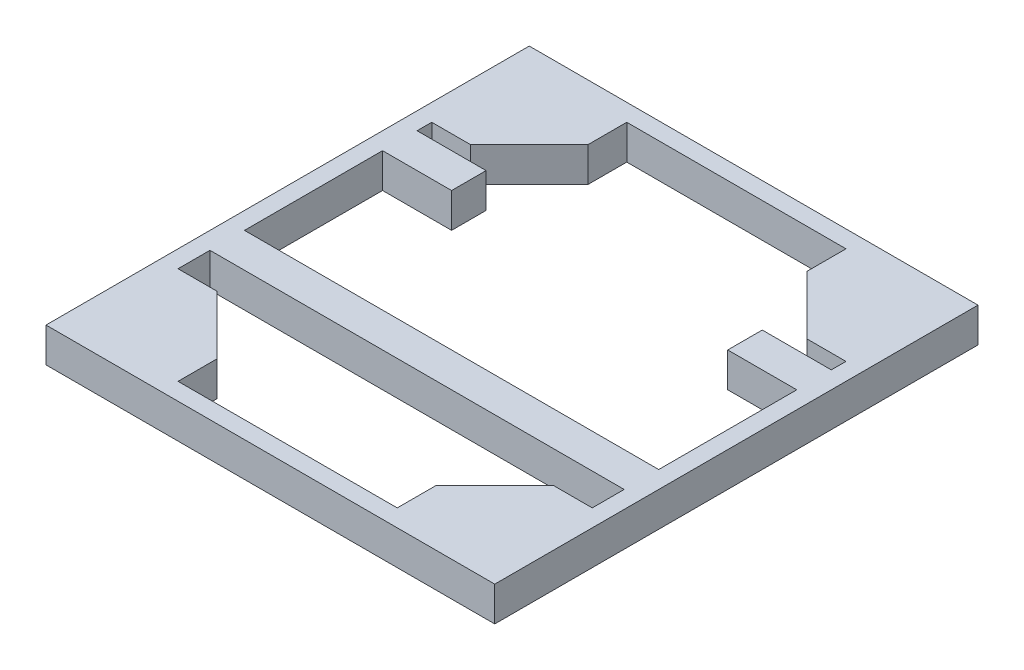
SolidWorks part; units mm, degrees
ref_plane "Front Plane" through (0, 0, 0) normal (0, 0, 1) x (1, 0, 0)
ref_plane "Top Plane" through (0, 0, 0) normal (0, 1, 0) x (1, 0, 0)
ref_plane "Right Plane" through (0, 0, 0) normal (1, 0, 0) x (0, 0, -1)
sketch "Sketch1" plane through (0, 0, 0) normal (0, 1, 0) x (1, 0, 0)
  line L0 (82.55, 542.3028) -> (168.8972, 628.65)
  line L1 (0, 0) -> (660.4, 0)
  line L2 (0, 0) -> (0, 711.2)
  line L3 (0, 711.2) -> (660.4, 711.2)
  line L4 (660.4, 0) -> (660.4, 711.2)
  line L5 (25.4, 685.8) -> (635, 685.8)
  line L6 (25.4, 685.8) -> (25.4, 25.4)
  line L7 (25.4, 25.4) -> (635, 25.4)
  line L8 (635, 685.8) -> (635, 25.4)
  line L9 (82.55, 542.3028) -> (25.4, 542.3028)
  line L10 (168.8972, 628.65) -> (168.8972, 685.8)
  line L11 (330.2, 711.2) -> (330.2, 0) construction
  line L12 (0, 355.6) -> (660.4, 355.6) construction
  line L13 (82.55, 168.8972) -> (168.8972, 82.55)
  line L14 (168.8972, 82.55) -> (168.8972, 25.4)
  line L15 (82.55, 168.8972) -> (25.4, 168.8972)
  line L16 (491.5028, 628.65) -> (491.5028, 685.8)
  line L17 (577.85, 542.3028) -> (491.5028, 628.65)
  line L18 (577.85, 542.3028) -> (635, 542.3028)
  line L19 (577.85, 168.8972) -> (635, 168.8972)
  line L20 (491.5028, 82.55) -> (491.5028, 25.4)
  line L21 (577.85, 168.8972) -> (491.5028, 82.55)
  point P9 (330.2, 685.8)
  point P10 (330.2, 711.2)
  point P11 (635, 355.6)
  point P12 (660.4, 355.6)
  dimension "D1" = 660.4
  dimension "D2" = 711.2
  dimension "D3" = 25.4
  dimension "D4" = 25.4
  dimension "D5" = 177.8
  dimension "D6" = 57.15
  dimension "D7" = 57.15
  dimension "D8" = 45
extrude "Boss-Extrude1" add sketch "Sketch1" along normal blind 50.8 contours L0 L10 L5 L6 L9 | L17 L18 L8 L5 L16 | L19 L21 L20 L7 L8 | L13 L15 L6 L7 L14 | L1 L4 L3 L2 L5 L8 L7 L6
sketch "Sketch2" plane through (0, 50.8, 0) normal (0, 1, 0) x (1, 0, 0)
  line L1 (635, 215.9) -> (25.4, 215.9)
  line L2 (635, 215.9) -> (635, 266.7)
  line L3 (635, 266.7) -> (25.4, 266.7)
  line L4 (25.4, 215.9) -> (25.4, 266.7)
  line L5 (635, 469.9) -> (25.4, 469.9)
  line L6 (635, 469.9) -> (635, 520.7)
  line L7 (635, 520.7) -> (25.4, 520.7)
  line L8 (25.4, 469.9) -> (25.4, 520.7)
  line L16 (168.8972, 25.4) -> (491.5028, 25.4)
  line L17 (168.8972, 82.55) -> (168.8972, 25.4)
  line L18 (82.55, 168.8972) -> (168.8972, 82.55)
  line L19 (25.4, 168.8972) -> (82.55, 168.8972)
  line L20 (25.4, 542.3028) -> (25.4, 168.8972)
  line L21 (82.55, 542.3028) -> (25.4, 542.3028)
  line L22 (168.8972, 628.65) -> (82.55, 542.3028)
  line L23 (168.8972, 685.8) -> (168.8972, 628.65)
  line L24 (491.5028, 685.8) -> (168.8972, 685.8)
  line L25 (491.5028, 628.65) -> (491.5028, 685.8)
  line L26 (577.85, 542.3028) -> (491.5028, 628.65)
  line L27 (635, 542.3028) -> (577.85, 542.3028)
  line L28 (635, 168.8972) -> (635, 542.3028)
  line L29 (577.85, 168.8972) -> (635, 168.8972)
  line L30 (491.5028, 82.55) -> (577.85, 168.8972)
  line L31 (491.5028, 25.4) -> (491.5028, 82.55)
  line L32 (168.8972, 25.4) -> (491.5028, 25.4)
  line L33 (168.8972, 82.55) -> (168.8972, 25.4)
  line L34 (82.55, 168.8972) -> (168.8972, 82.55)
  line L35 (25.4, 168.8972) -> (82.55, 168.8972)
  line L36 (25.4, 542.3028) -> (25.4, 168.8972)
  line L37 (82.55, 542.3028) -> (25.4, 542.3028)
  line L38 (168.8972, 628.65) -> (82.55, 542.3028)
  line L39 (168.8972, 685.8) -> (168.8972, 628.65)
  line L40 (491.5028, 685.8) -> (168.8972, 685.8)
  line L41 (491.5028, 628.65) -> (491.5028, 685.8)
  line L42 (577.85, 542.3028) -> (491.5028, 628.65)
  line L43 (635, 542.3028) -> (577.85, 542.3028)
  line L44 (635, 168.8972) -> (635, 542.3028)
  line L45 (577.85, 168.8972) -> (635, 168.8972)
  line L46 (491.5028, 82.55) -> (577.85, 168.8972)
  line L47 (491.5028, 25.4) -> (491.5028, 82.55)
  point P18 (25.4, 355.6)
  line M25 (25.4, 168.8972) -> (25.4, 542.3028)
  line M33 (635, 542.3028) -> (635, 168.8972)
  dimension "D2" = 50.8
  dimension "D3" = 50.8
  dimension "D4" = 88.9
  dimension "D5" = 114.3
  dimension "D1" = 0
extrude "Boss-Extrude2" add sketch "Sketch2" against normal blind 50.8 contours L3 L1 M33 M25 | L7 L5 M33 M25
sketch "Sketch3" plane through (0, 50.8, 0) normal (0, 1, 0) x (1, 0, 0)
  line L0 (635, 469.9) -> (25.4, 469.9) construction
  line L1 (533.4, 469.9) -> (127, 469.9)
  line L2 (533.4, 469.9) -> (533.4, 520.7)
  line L3 (533.4, 520.7) -> (127, 520.7)
  line L4 (127, 469.9) -> (127, 520.7)
  line L5 (635, 520.7) -> (25.4, 520.7) construction
  line L6 (25.4, 469.9) -> (25.4, 266.7) construction
  dimension "D1" = 101.6
  dimension "D2" = 406.4
extrude "Cut-Extrude2" cut sketch "Sketch3" against normal through all
